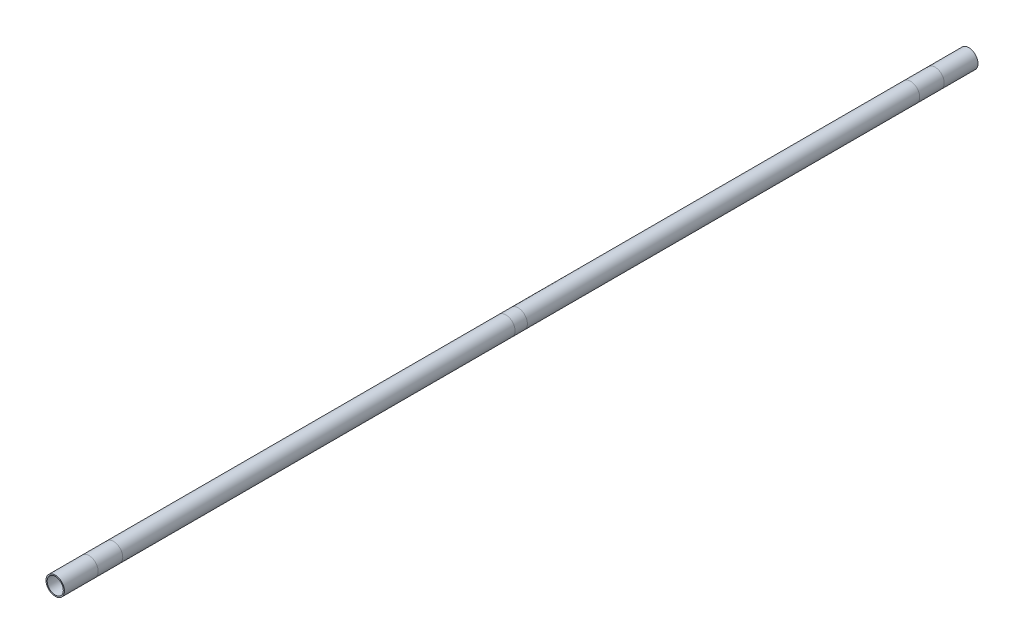
SolidWorks part; units mm, degrees
material "AISI Type 316L stainless steel"
ref_plane "Front Plane" through (0, 0, 0) normal (0, 0, 1) x (1, 0, 0)
ref_plane "Top Plane" through (0, 0, 0) normal (0, 1, 0) x (1, 0, 0)
ref_plane "Right Plane" through (0, 0, 0) normal (1, 0, 0) x (0, 0, -1)
sketch "Pipe section 60.3 x 3.91" plane through (0, 0, 0) normal (0, 0, 1) x (1, 0, 0)
  circle A0 centre (0, 0) radius 30.15
  circle A1 centre (0, 0) radius 26.24
extrude "Guide pole 2in Sch 40S" add sketch "Pipe section 60.3 x 3.91" along normal blind 2978
sketch "Clamp and roller bands" plane through (0, 0, 0) normal (1, 0, 0) x (0, 0, -1)
  line L0 (-110, -80) -> (-110, 80)
  line L1 (-190, -80) -> (-190, 80)
  line L2 (-2788, -80) -> (-2788, 80)
  line L3 (-2868, -80) -> (-2868, 80)
  line L4 (-1469, -80) -> (-1469, 80)
  line L5 (-1509, -80) -> (-1509, 80)
split line "Split Line1"
